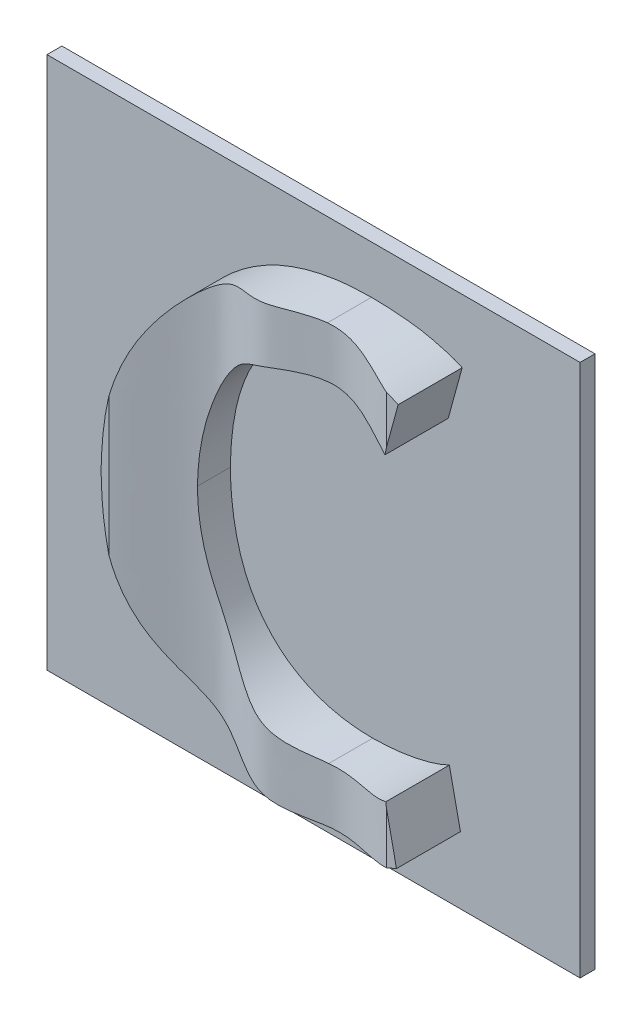
SolidWorks part; units mm, degrees
ref_plane "Top Plane" through (0, 0, 0) normal (0, 0, 1) x (1, 0, 0)
ref_plane "Right Plane" through (0, 0, 0) normal (0, 1, 0) x (1, 0, 0)
ref_plane "Front Plane" through (0, 0, 0) normal (1, 0, 0) x (0, 0, -1)
sketch "Sketch1" plane through (0, 0, 0) normal (0, 0, 1) x (1, 0, 0)
  line L1 (-25, -25) -> (25, -25)
  line L2 (-25, -25) -> (-25, 25)
  line L3 (-25, 25) -> (25, 25)
  line L4 (25, -25) -> (25, 25)
  line L5 (-25, -25) -> (25, 25) construction
  line L6 (-25, 25) -> (25, -25) construction
  point P0 (0, 0)
  dimension "D1" = 50
extrude "Boss-Extrude1" add sketch "Sketch1" along normal blind 1.4
sketch "Sketch2" plane through (0, 0, 1.4) normal (0, 0, 1) x (1, 0, 0)
  line L0 (-25, -20) -> (25, -20) construction
  line L1 (-25, 25) -> (-25, -25) construction
  line L2 (25, -25) -> (25, 25) construction
  line L3 (-25, -25) -> (25, -25) construction
  text T0 "A" font "Kozuka Gothic Pr6N M" height 40
  dimension "D1" = 5
extrude "Boss-Extrude2" [suppressed] add sketch "Sketch2" along normal blind 6
sketch "Sketch4" [suppressed] plane through (0, 0, 4) normal (0, 0, 1) x (1, 0, 0)
  line L0 (-25, -20) -> (25, -20) construction
  line L1 (-25, 25) -> (-25, -25) construction
  line L2 (25, -25) -> (25, 25) construction
  line L5 (-25, -25) -> (25, -25) construction
  text T0 "B" font "Kozuka Gothic Pr6N M" height 40
  dimension "D1" = 5
extrude "Boss-Extrude3" [suppressed] add sketch "Sketch4" along normal blind 6
sketch "Sketch6" plane through (0, 0, 1.4) normal (0, 0, 1) x (1, 0, 0)
  line L0 (-25, -20) -> (25, -20) construction
  line L1 (-25, 25) -> (-25, -25) construction
  line L2 (25, -25) -> (25, 25) construction
  line L3 (-25, -25) -> (25, -25) construction
  text T0 "C" font "Kozuka Gothic Pr6N M" height 40
  dimension "D1" = 5
extrude "Boss-Extrude4" add sketch "Sketch6" along normal blind 6
sketch "Sketch5" [suppressed] plane through (0, -25, 0) normal (0, -1, 0) x (1, 0, 0)
  line L0 (-25, 4) -> (25, 4) construction
  line L1 (-16, 4) -> (16, 4) construction
  line L2 (-16, 4) -> (-16, 10) construction
  line L3 (-16, 10) -> (16, 10)
  line L4 (16, 4) -> (16, 10) construction
  line L5 (0, 4) -> (0, 0) construction
  line L6 (-25, 0) -> (25, 0) construction
  arc A0 (-16, 10) -> (16, 10) centre (0, 51.1667) ccw
  point P11 (0, 7)
  dimension "D3" = 3
  dimension "D1" = 32
  dimension "D2" = 6
extrude "Cut-Extrude1" [suppressed] cut sketch "Sketch5" against normal through all
sketch "Sketch7" [suppressed] plane through (0, -25, 0) normal (0, -1, 0) x (1, 0, 0)
  line L1 (-17.5, 4) -> (17.5, 4) construction
  line L2 (-17.5, 4) -> (-17.5, 14)
  line L3 (-17.5, 14) -> (17.5, 14)
  line L4 (17.5, 4) -> (17.5, 14)
  line L5 (-25, 4) -> (25, 4) construction
  line L6 (0, 14) -> (0, 0) construction
  line L8 (-25, 0) -> (25, 0) construction
  arc A0 (-17.5, 4) -> (17.5, 4) centre (0, -18.5208) cw
  point P4 (0, 10)
  point P18 (0, 4)
  dimension "D1" = 6
  dimension "D2" = 10
  dimension "D3" = 35
extrude "Cut-Extrude2" [suppressed] cut sketch "Sketch7" against normal through all
sketch "Sketch8" plane through (0, -25, 0) normal (0, -1, 0) x (1, 0, 0)
  line L0 (-25, 1.4) -> (25, 1.4) construction
  line L1 (-17.5, 1.4) -> (17.5, 1.4) construction
  line L2 (-17.5, 1.4) -> (-17.5, 8.4)
  line L4 (17.5, 1.4) -> (17.5, 8.4)
  line L5 (0, 1.4) -> (0, 0) construction
  line L6 (-25, 0) -> (25, 0) construction
  line L7 (-11.6667, 8.4) -> (-11.6667, 6.6) construction
  line L8 (-17.5, 8.4) -> (-11.6667, 8.4)
  line L9 (-5.8333, 4.2) -> (-5.8333, 8.4) construction
  line L10 (-11.6667, 8.4) -> (-5.8333, 8.4)
  line L11 (0, 6.3) -> (0, 8.4) construction
  line L12 (-5.8333, 8.4) -> (0, 8.4)
  line L13 (5.8333, 5.5) -> (5.8333, 8.4) construction
  line L14 (0, 8.4) -> (5.8333, 8.4)
  line L15 (11.6667, 7) -> (11.6667, 8.4) construction
  line L16 (5.8333, 8.4) -> (11.6667, 8.4)
  line L17 (11.6667, 8.4) -> (17.5, 8.4)
  spline S0 degree 3 poles (-17.5, 1.4) (-17.5, 9.5719) (-11.7546, 7.0007) (-5.9546, 2.7069) (-0.1813, 7.5862) (5.9776, 4.5935) (12.1025, 7.3638) (17.5, 8.8904) (17.5, 1.4) knots 0 0 0 0 0.193817 0.350261 0.504029 0.650061 0.799445 1 1 1 1
  point P23 (17.5, 11.8128)
  dimension "D1" = 7
  dimension "D2" = 35
  dimension "D3" = 1.8
  dimension "D4" = 4.2
  dimension "D5" = 2.1
  dimension "D6" = 2.9
  dimension "D7" = 1.4
extrude "Cut-Extrude3" cut sketch "Sketch8" against normal through all
